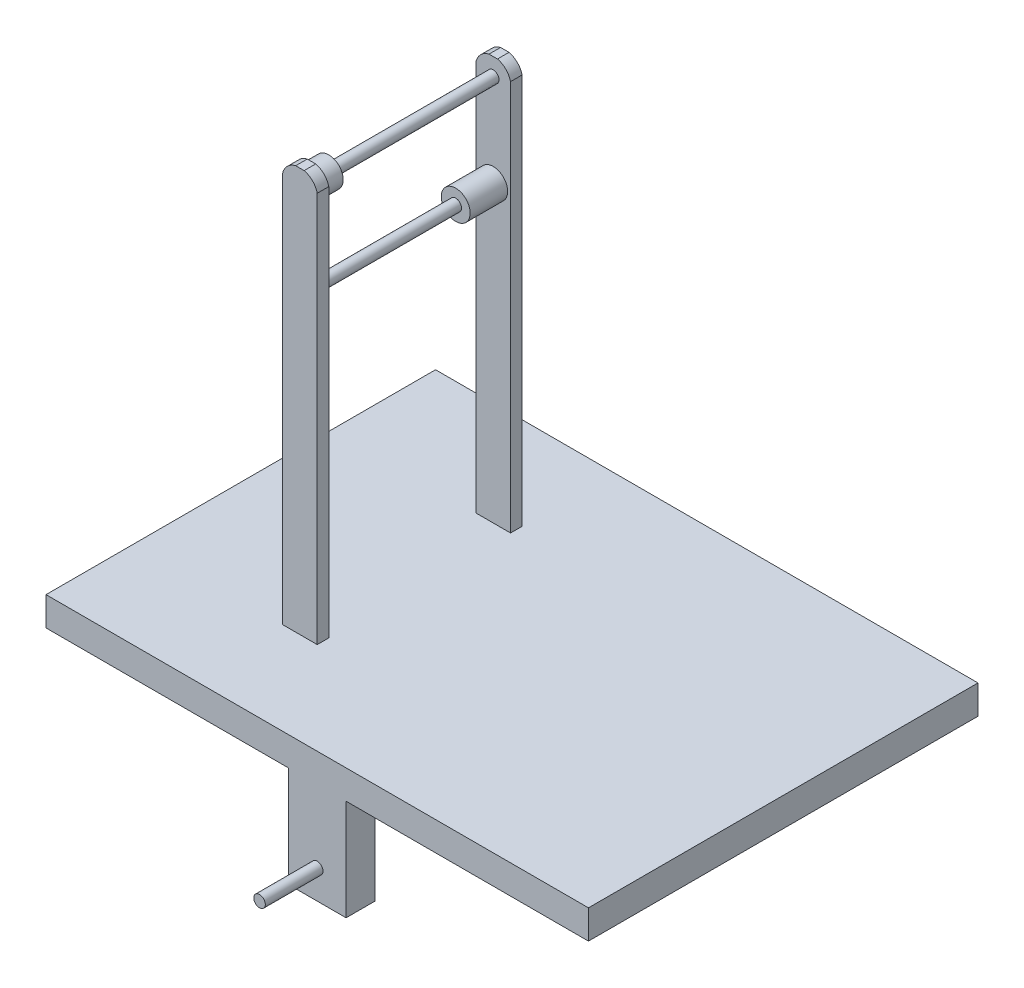
SolidWorks part; units mm, degrees
ref_plane "Plan de face" through (0, 0, 0) normal (0, 0, 1) x (1, 0, 0)
ref_plane "Plan de dessus" through (0, 0, 0) normal (0, 1, 0) x (1, 0, 0)
ref_plane "Plan de droite" through (0, 0, 0) normal (1, 0, 0) x (0, 0, -1)
sketch "Esquisse1" plane through (0, 0, 0) normal (0, 1, 0) x (1, 0, 0)
  line L1 (0, 0) -> (188, 0)
  line L2 (0, 0) -> (0, 135)
  line L3 (0, 135) -> (188, 135)
  line L4 (188, 0) -> (188, 135)
  dimension "D1" = 188
  dimension "D2" = 135
extrude "Boss.-Extru.1" add sketch "Esquisse1" along normal blind 10
sketch "Esquisse2" plane through (0, 10, 0) normal (0, 1, 0) x (1, 0, 0)
  line L0 (0, 0) -> (188, 0) construction
  line L1 (50, 32) -> (62, 32)
  line L2 (50, 32) -> (50, 103)
  line L3 (50, 103) -> (62, 103)
  line L4 (62, 32) -> (62, 103)
  line L5 (188, 135) -> (0, 135) construction
  line L6 (0, 135) -> (0, 0) construction
  dimension "D1" = 12
  dimension "D2" = 32
  dimension "D3" = 32
  dimension "D4" = 50
extrude "Boss.-Extru.2" add sketch "Esquisse2" along normal blind 140
sketch "Esquisse4" plane through (62, 0, 0) normal (1, 0, 0) x (0, 0, -1)
  line L0 (32, 150) -> (103, 150) construction
  line L1 (36, 150) -> (99, 150)
  line L2 (36, 150) -> (36, 10)
  line L3 (36, 10) -> (99, 10)
  line L4 (99, 150) -> (99, 10)
  line L5 (32, 10) -> (103, 10) construction
  line L6 (32, 150) -> (32, 10) construction
  line L7 (103, 150) -> (103, 10) construction
  dimension "D1" = 4
  dimension "D2" = 4
extrude "Enlèv. mat.-Extru.1" cut sketch "Esquisse4" against normal blind 140
sketch "Esquisse6" plane through (0, 0, -99) normal (0, 0, 1) x (1, 0, 0)
  line L0 (62, 10) -> (62, 150) construction
  line L1 (50, 150) -> (62, 150) construction
  circle A0 centre (56, 144) radius 2
  dimension "D3" = 4
  dimension "D1" = 6
  dimension "D2" = 6
extrude "Boss.-Extru.3" add sketch "Esquisse6" along normal blind 67
sketch "Esquisse7" plane through (0, 0, -32) normal (0, 0, 1) x (1, 0, 0)
  line L0 (62, 150) -> (62, 10) construction
  line L1 (50, 150) -> (50, 10) construction
  line L2 (50, 150) -> (62, 150) construction
  line L3 (50, 145.4691) -> (50, 152.7444)
  line L4 (50, 152.7444) -> (62, 152.7444)
  line L5 (62, 152.7444) -> (62, 145.4691)
  arc A0 (62, 145.4691) -> (50, 145.4691) centre (56, 144) ccw
  dimension "D1" = 6
  dimension "D2" = 6
extrude "Enlèv. mat.-Extru.2" cut sketch "Esquisse7" against normal through all contours L4 L5 A0 L3
sketch "Esquisse11" plane through (0, 0, 0) normal (0, -1, 0) x (1, 0, 0)
  line L0 (0, 0) -> (188, 0) construction
  line L1 (84, 0) -> (104, 0)
  line L2 (84, 0) -> (84, -10)
  line L3 (84, -10) -> (104, -10)
  line L4 (104, 0) -> (104, -10)
  line L5 (0, -135) -> (0, 0) construction
  line L6 (188, 0) -> (188, -135) construction
  dimension "D1" = 84
  dimension "D2" = 84
  dimension "D3" = 10
extrude "Boss.-Extru.4" add sketch "Esquisse11" along normal blind 35
sketch "Esquisse12" plane through (0, 0, 0) normal (0, 0, 1) x (1, 0, 0)
  line L0 (0, 0) -> (84, 0) construction
  line L1 (104, -35) -> (104, 0) construction
  circle A0 centre (94, -25) radius 2
  dimension "D2" = 4
  dimension "D1" = 25
  dimension "D3" = 10
extrude "Boss.-Extru.5" add sketch "Esquisse12" along normal blind 20
sketch "Esquisse13" plane through (0, 0, 0) normal (0, -1, 0) x (1, 0, 0)
  line L0 (188, -135) -> (0, -135) construction
  line L1 (104, -135) -> (84, -135)
  line L2 (104, -135) -> (104, -125)
  line L3 (104, -125) -> (84, -125)
  line L4 (84, -135) -> (84, -125)
  line L5 (104, -10) -> (104, 0) construction
  line L6 (84, 0) -> (84, -10) construction
  dimension "D1" = 0
  dimension "D2" = 0
  dimension "D3" = 10
extrude "Boss.-Extru.6" add sketch "Esquisse13" along normal blind 35
sketch "Esquisse14" plane through (0, 0, -135) normal (0, 0, -1) x (-1, 0, 0)
  line L0 (-84, -35) -> (-104, -35) construction
  line L1 (-104, -35) -> (-104, 0) construction
  circle A0 centre (-94, -25) radius 2
  dimension "D1" = 4
  dimension "D2" = 10
  dimension "D3" = 10
extrude "Boss.-Extru.7" add sketch "Esquisse14" along normal blind 20
sketch "Esquisse15" plane through (0, 0, -99) normal (0, 0, 1) x (1, 0, 0)
  line L0 (62, 10) -> (62, 145.4691) construction
  circle A0 centre (56, 112) radius 2
  circle A1 centre (56, 144) radius 2 construction
  dimension "D1" = 32
  dimension "D2" = 4
  dimension "D3" = 6
extrude "Boss.-Extru.8" add sketch "Esquisse15" along normal blind 67
sketch "Esquisse16" plane through (0, 0, -99) normal (0, 0, 1) x (1, 0, 0)
  circle A0 centre (56, 112) radius 5
  dimension "D1" = 10
extrude "Boss.-Extru.9" add sketch "Esquisse16" along normal blind 13
sketch "Esquisse17" plane through (0, 0, -36) normal (0, 0, -1) x (-1, 0, 0)
  circle A0 centre (-56, 144) radius 5
  dimension "D1" = 10
extrude "Boss.-Extru.10" add sketch "Esquisse17" along normal blind 6
